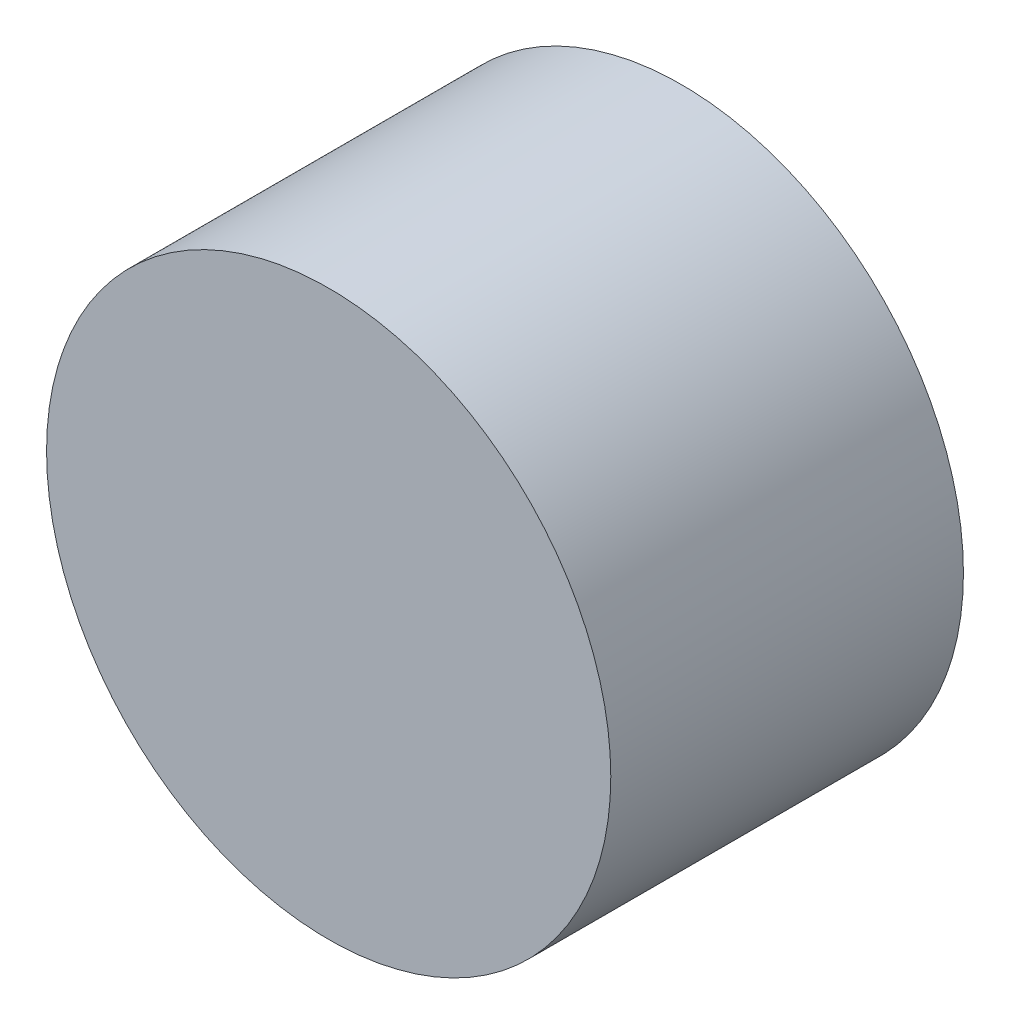
SolidWorks part; units mm, degrees
ref_plane "Front Plane" through (0, 0, 0) normal (0, 0, 1) x (1, 0, 0)
ref_plane "Top Plane" through (0, 0, 0) normal (0, 1, 0) x (1, 0, 0)
ref_plane "Right Plane" through (0, 0, 0) normal (1, 0, 0) x (0, 0, -1)
sketch "Sketch1" plane through (0, 0, 0) normal (0, 0, 1) x (1, 0, 0)
  circle A0 centre (0, 0) radius 10
  dimension "D1" = 20
extrude "Boss-Extrude1" add sketch "Sketch1" along normal blind 12.5
